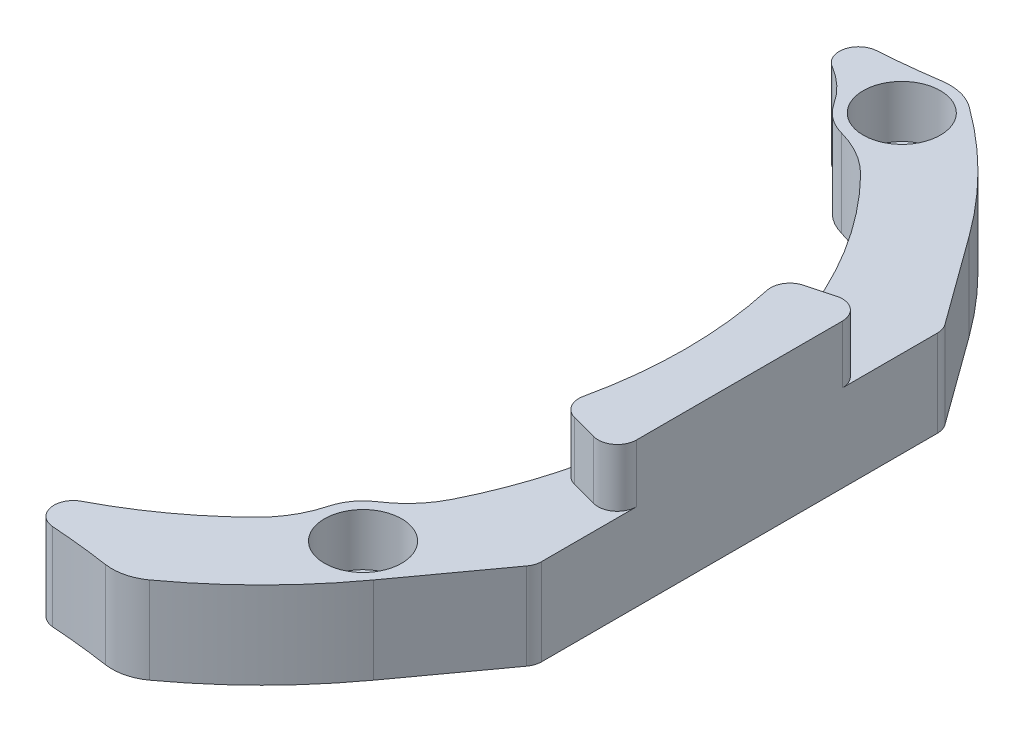
SolidWorks part; units mm, degrees
material "6061 合金"
ref_plane "前视基准面" through (0, 0, 0) normal (0, 0, 1) x (1, 0, 0)
ref_plane "上视基准面" through (0, 0, 0) normal (0, 1, 0) x (1, 0, 0)
ref_plane "右视基准面" through (0, 0, 0) normal (1, 0, 0) x (0, 0, -1)
other "Configuration Table"
sketch "草图1" plane through (0, 0, 0) normal (0, 1, 0) x (1, 0, 0)
  line L0 (0, 0) -> (36.1587, 0) construction
  arc A161 (21.6874, 13.5954) -> (21.2367, 15.4294) centre (19.2142, 13.9599) ccw construction
  arc A162 (21.6874, 13.5954) -> (21.5774, 2.7345) centre (61.26, 7.7635) ccw construction
  arc A163 (2.7345, 21.5774) -> (7.7635, 21.26) centre (7.7635, 61.26) ccw construction
  arc A164 (7.7635, 21.26) -> (13.5954, 21.6874) centre (7.7635, 61.26) ccw construction
  arc A165 (15.4294, 21.2367) -> (13.5954, 21.6874) centre (13.9599, 19.2142) ccw construction
  arc A166 (21.2367, 15.4294) -> (15.4294, 21.2367) centre (0, 0) ccw construction
  arc A167 (21.6874, 13.5954) -> (21.2367, 15.4294) centre (19.2142, 13.9599) ccw
  arc A168 (21.6874, 13.5954) -> (21.3486, 5.1029) centre (61.26, 7.7635) ccw
  arc A169 (5.1029, 21.3486) -> (7.7635, 21.26) centre (7.7635, 61.26) ccw
  arc A170 (7.7635, 21.26) -> (13.5954, 21.6874) centre (7.7635, 61.26) ccw
  arc A171 (15.4294, 21.2367) -> (13.5954, 21.6874) centre (13.9599, 19.2142) ccw
  arc A172 (21.2367, 15.4294) -> (15.4294, 21.2367) centre (0, 0) ccw
  circle A184 centre (13.9599, 19.2142) radius 1.025
  arc A212 (19.655, -9.7715) -> (15.6735, 15.367) centre (0, 0) ccw
  arc A213 (15.6735, 15.367) -> (13.302, 16.7505) centre (11.9604, 11.7265) ccw
  arc A214 (11.8201, 17.8271) -> (13.302, 16.7505) centre (13.9599, 19.2142) ccw
  arc A215 (11.8201, 17.8271) -> (9.7715, 19.655) centre (7.4566, 14.9987) ccw
  arc A216 (9.7715, 19.655) -> (-15.367, 15.6735) centre (0, 0) ccw
  arc A217 (21.3486, 5.1029) -> (15.6735, 15.367) centre (0, 0) ccw
  arc A218 (15.6735, 15.367) -> (13.302, 16.7505) centre (11.9604, 11.7265) ccw
  arc A219 (11.8201, 17.8271) -> (13.302, 16.7505) centre (13.9599, 19.2142) ccw
  arc A220 (11.8201, 17.8271) -> (9.7715, 19.655) centre (7.4566, 14.9987) ccw
  arc A221 (9.7715, 19.655) -> (5.1029, 21.3486) centre (0, 0) ccw
  arc A249 (13.5954, -21.6874) -> (13.9599, -21.7142) centre (13.9599, -19.2142) ccw construction
  arc A250 (13.5954, -21.6874) -> (2.7345, -21.5774) centre (7.7635, -61.26) ccw construction
  arc A251 (13.9599, -21.7142) -> (15.4294, -21.2367) centre (13.9599, -19.2142) ccw construction
  arc A252 (15.4294, -21.2367) -> (21.2367, -15.4294) centre (0, 0) ccw construction
  arc A253 (21.2367, -15.4294) -> (21.6874, -13.5954) centre (19.2142, -13.9599) ccw construction
  arc A254 (19.655, -9.7715) -> (15.6735, 15.367) centre (0, 0) ccw
  arc A255 (0, -21.95) -> (15.367, -15.6735) centre (0, 0) ccw
  arc A256 (15.367, -15.6735) -> (16.7505, -13.302) centre (11.7265, -11.9604) ccw
  arc A257 (17.8271, -11.8201) -> (16.7505, -13.302) centre (19.2142, -13.9599) ccw
  arc A258 (17.8271, -11.8201) -> (19.655, -9.7715) centre (14.9987, -7.4566) ccw
  arc A259 (19.655, -9.7715) -> (21.3486, -5.1029) centre (0, 0) ccw
  arc A260 (5.1029, -21.3486) -> (15.367, -15.6735) centre (0, 0) ccw
  arc A261 (15.367, -15.6735) -> (16.7505, -13.302) centre (11.7265, -11.9604) ccw
  arc A262 (17.8271, -11.8201) -> (16.7505, -13.302) centre (19.2142, -13.9599) ccw
  arc A263 (17.8271, -11.8201) -> (19.655, -9.7715) centre (14.9987, -7.4566) ccw
  arc A264 (21.5774, -2.7345) -> (21.6874, -13.5954) centre (61.26, -7.7635) ccw construction
  arc A265 (13.5954, -21.6874) -> (13.9599, -21.7142) centre (13.9599, -19.2142) ccw
  arc A266 (13.5954, -21.6874) -> (5.1029, -21.3486) centre (7.7635, -61.26) ccw
  arc A267 (13.9599, -21.7142) -> (15.4294, -21.2367) centre (13.9599, -19.2142) ccw
  arc A268 (15.4294, -21.2367) -> (21.2367, -15.4294) centre (0, 0) ccw
  arc A269 (21.2367, -15.4294) -> (21.6874, -13.5954) centre (19.2142, -13.9599) ccw
  arc A270 (21.3486, -5.1029) -> (21.6874, -13.5954) centre (61.26, -7.7635) ccw
  arc A271 (19.2142, -15.4099) -> (19.2142, -12.5099) centre (19.2142, -13.9599) ccw construction
  arc A272 (19.2142, -12.5099) -> (19.2142, -15.4099) centre (19.2142, -13.9599) ccw construction
  arc A273 (19.2142, -15.4099) -> (19.2142, -12.5099) centre (19.2142, -13.9599) ccw
  arc A274 (19.2142, -12.5099) -> (19.2142, -15.4099) centre (19.2142, -13.9599) ccw
  arc A275 (21.3486, 5.1029) -> (15.6735, 15.367) centre (0, 0) ccw
  dimension "D1" = 2.05
  dimension "D2" = 0.2
  dimension "D3" = 0.2
extrude "凸台-拉伸1" add sketch "草图1" along normal blind 4.5
sketch "草图4" plane through (0, 4.5, 0) normal (0, 1, 0) x (1, 0, 0)
  line L0 (0, 0) -> (32.7858, 0) construction
  line L1 (21.2367, -15.4294) -> (24.7634, -10.5753)
  line L2 (24.7634, -10.5753) -> (24.7634, 10.5753)
  line L3 (21.2367, 15.4294) -> (24.7634, 10.5753)
  arc A0 (21.6874, 13.5954) -> (21.2367, 15.4294) centre (19.2142, 13.9599) ccw construction
  arc A1 (21.2367, -15.4294) -> (21.6874, -13.5954) centre (19.2142, -13.9599) ccw construction
  arc A2 (21.6874, 13.5954) -> (21.3486, 5.1029) centre (61.26, 7.7635) ccw construction
  arc A3 (19.655, -9.7715) -> (15.6735, 15.367) centre (0, 0) ccw
  arc A4 (21.3486, -5.1029) -> (21.3486, 5.1029) centre (0, 0) ccw
  arc A5 (21.3486, -5.1029) -> (21.6874, -13.5954) centre (61.26, -7.7635) ccw construction
  arc A6 (21.6874, 13.5954) -> (21.3486, 5.1029) centre (61.26, 7.7635) ccw
  arc A7 (21.3486, -5.1029) -> (21.6874, -13.5954) centre (61.26, -7.7635) ccw
  arc A9 (21.6874, 13.5954) -> (21.2367, 15.4294) centre (19.2142, 13.9599) ccw
  arc A10 (21.2367, -15.4294) -> (21.6874, -13.5954) centre (19.2142, -13.9599) ccw
  point P16 (24.7634, 0)
  dimension "D2" = 6
  dimension "D1" = 0.2
extrude "凸台-拉伸2" add sketch "草图4" against normal up to surface (4.5 mm away) up to face at (19.2142, 0, 15.4099)
sketch "草图5" plane through (0, 4.5, 0) normal (0, 1, 0) x (1, 0, 0)
  line L0 (0, 0) -> (29.9967, 0) construction
  line L1 (21.2021, -5.6811) -> (24.7634, -6.6353)
  line L2 (24.7634, -10.5753) -> (24.7634, 10.5753) construction
  line L3 (21.2021, 5.6811) -> (24.7634, 6.6353)
  line L4 (24.7634, -6.6353) -> (24.7634, 6.6353)
  arc A0 (19.655, -9.7715) -> (15.6735, 15.367) centre (0, 0) ccw construction
  arc A1 (21.2021, -5.6811) -> (21.2021, 5.6811) centre (0, 0) ccw
  dimension "D1" = 15
extrude "凸台-拉伸3" add sketch "草图5" along normal blind 3
sketch "草图6" plane through (0, 7.5, 0) normal (0, 1, 0) x (1, 0, 0)
  line L0 (24.7634, -6.6353) -> (18.3043, -4.9046)
  line L1 (24.7634, 6.6353) -> (18.3043, 4.9046)
  line L2 (24.7634, -6.6353) -> (24.7634, 6.6353)
  arc A2 (18.3043, -4.9046) -> (18.3043, 4.9046) centre (0, 0) ccw
  arc A3 (18.3043, -4.9046) -> (18.3043, 4.9046) centre (0, 0) ccw
  dimension "D1" = 3
extrude "凸台-拉伸4" [suppressed] add sketch "草图6" against normal blind 3
fillet "圆角2" [suppressed] radius 1
sketch "草图7" plane through (0, 4.5, 0) normal (0, 1, 0) x (1, 0, 0)
  circle A0 centre (19.2142, -13.9599) radius 1
  circle A1 centre (19.2142, -13.9599) radius 1.45 construction
  circle A2 centre (19.2142, -13.9599) radius 1.45
  dimension "D1" = 2
extrude "凸台-拉伸5" add sketch "草图7" against normal up to surface (4.5 mm away) up to face at (15.8728, 0, -1.0637)
hole_wizard "M2.5 六角圆柱头螺钉的柱形沉头孔2" positions "3D草图3" profile "草图12" counterbore size "M2.5" standard "GB" end condition through all
sketch3d "3D草图3"
  line L0 (13.9599, 4.5, -19.2142) -> (13.9599, 0, -19.2142) construction
  line L1 (19.2142, 0, 13.9599) -> (19.2142, 4.5, 13.9599) construction
  point P0 (13.9599, 4.5, -19.2142)
  point P4 (19.2142, 4.5, 13.9599)
sketch "草图12" plane through (13.9599, 4.5, -19.2142) normal (1, 0, 0) x (0, 0, 1)
  line L0 (0, 0) -> (0, 4.5)
  line L1 (0, 4.5) -> (1.45, 4.5)
  line L3 (1.45, 4.5) -> (1.45, 2.7)
  line L4 (1.45, 2.7) -> (2, 2.7)
  line L5 (2, 2.7) -> (2, 0)
  line L7 (2, 0) -> (0, 0)
  line L11 (0, -6.35) -> (0, 107.95) construction
  dimension "通孔孔直径" = 2.9
  dimension "通孔孔深度" = 4.5
  dimension "柱形沉头孔直径" = 4
  dimension "柱形沉头孔深度" = 2.7
fillet "圆角5" radius 1 8 edges at (24.7634, 2.25, 10.5753) (24.7634, 2.25, -10.5753) (24.7634, 6, -6.6353) (21.2021, 6, -5.6811) (21.2021, 6, 5.6811) (24.7634, 6, 6.6353) (5.1029, 2.25, 21.3486) (5.1029, 2.25, -21.3486)
